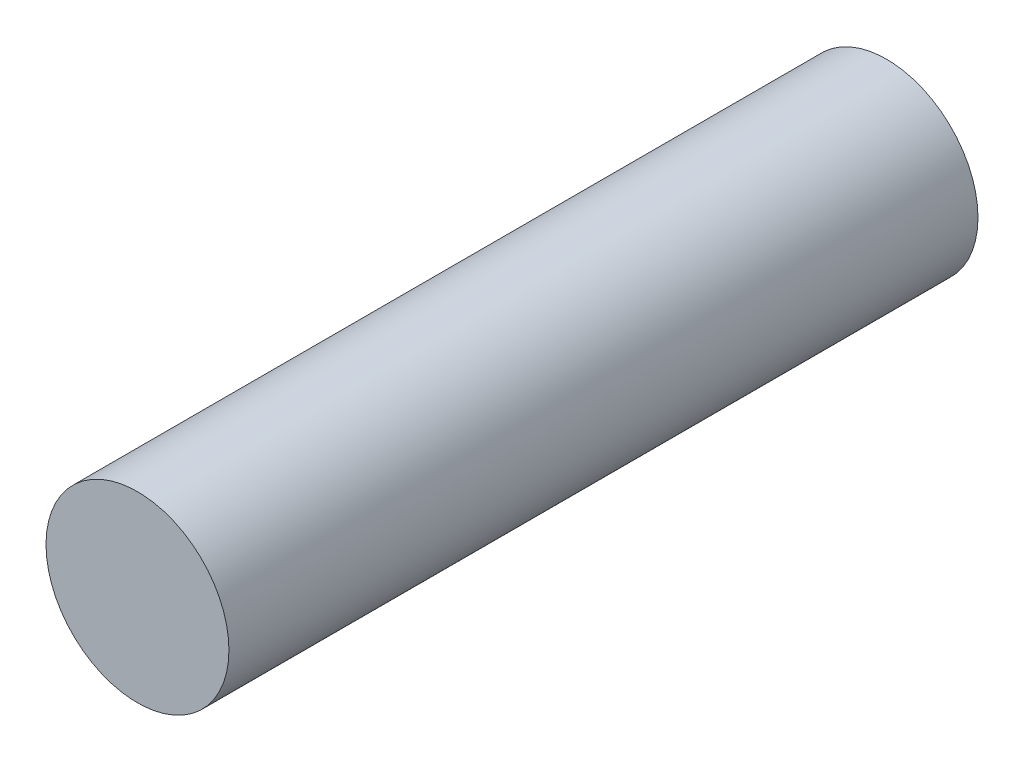
SolidWorks part; units mm, degrees
material "Titanium"
ref_plane "Front Plane" through (0, 0, 0) normal (0, 0, 1) x (1, 0, 0)
ref_plane "Top Plane" through (0, 0, 0) normal (0, 1, 0) x (1, 0, 0)
ref_plane "Right Plane" through (0, 0, 0) normal (1, 0, 0) x (0, 0, -1)
sketch "Sketch1" plane through (0, 0, 0) normal (0, 0, 1) x (1, 0, 0)
  circle A0 centre (0, 0) radius 3.175
  dimension "D1" = 6.35
extrude "Boss-Extrude1" add sketch "Sketch1" along normal up to surface (26.0007 mm away) contours A0
